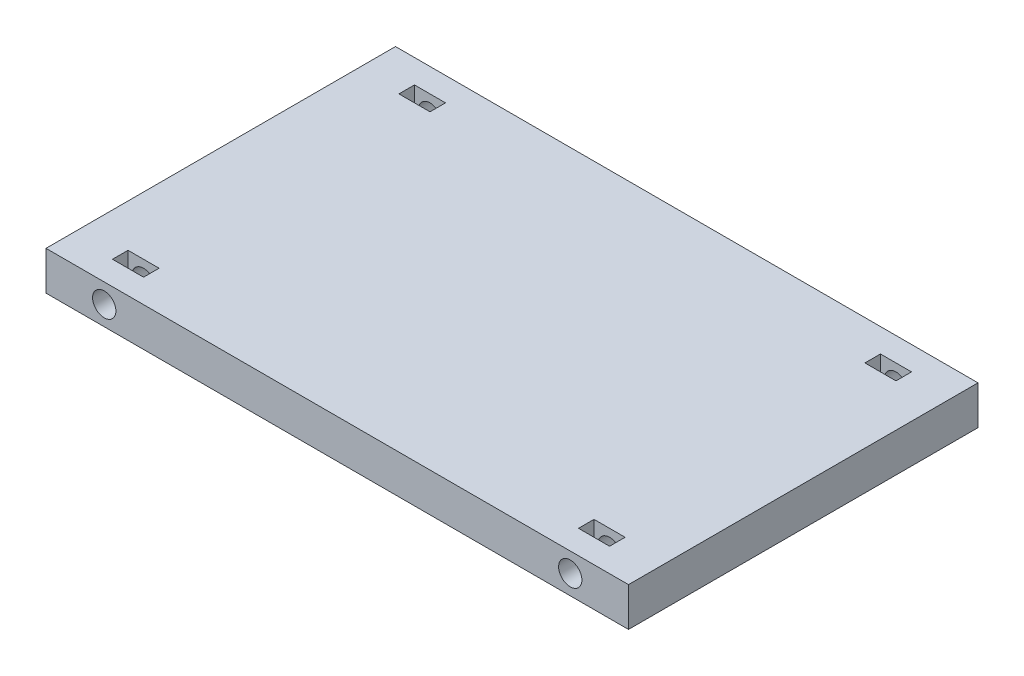
SolidWorks part; units mm, degrees
ref_plane "Front Plane" through (0, 0, 0) normal (0, 0, 1) x (1, 0, 0)
ref_plane "Top Plane" through (0, 0, 0) normal (0, 1, 0) x (1, 0, 0)
ref_plane "Right Plane" through (0, 0, 0) normal (1, 0, 0) x (0, 0, -1)
sketch "Sketch1" plane through (0, 0, 0) normal (0, 1, 0) x (1, 0, 0)
  line L0 (75, 90) -> (75, -10.3803) construction
  line L1 (0, 0) -> (150, 0)
  line L2 (0, 0) -> (0, 90)
  line L3 (0, 90) -> (150, 90)
  line L4 (150, 0) -> (150, 90)
  line L5 (75, -10.3803) -> (75, 39.8099) construction
  line L6 (0, 45) -> (160.1026, 45) construction
  line L7 (139, 10.1206) -> (139, 6.1206)
  line L8 (11, 83.8794) -> (19, 83.8794)
  line L9 (11, 83.8794) -> (11, 79.8794)
  line L10 (11, 79.8794) -> (19, 79.8794)
  line L11 (19, 83.8794) -> (19, 79.8794)
  line L12 (131, 79.8794) -> (139, 79.8794)
  line L13 (131, 79.8794) -> (131, 83.8794)
  line L14 (131, 83.8794) -> (139, 83.8794)
  line L15 (139, 79.8794) -> (139, 83.8794)
  line L16 (131, 6.1206) -> (139, 6.1206)
  line L17 (131, 10.1206) -> (131, 6.1206)
  line L18 (131, 10.1206) -> (139, 10.1206)
  line L19 (19, 6.1206) -> (19, 10.1206)
  line L20 (11, 10.1206) -> (19, 10.1206)
  line L21 (11, 6.1206) -> (11, 10.1206)
  line L22 (11, 6.1206) -> (19, 6.1206)
  point P14 (11, 81.8794)
  dimension "D1" = 90
  dimension "D2" = 150
  dimension "D3" = 4
  dimension "D4" = 8
  dimension "D5" = 11
  dimension "D6" = 8
  dimension "D7" = 112
extrude "Boss-Extrude1" add sketch "Sketch1" along normal blind 10
sketch "Sketch3" plane through (0, 0, 0) normal (0, 0, 1) x (1, 0, 0)
  line L1 (0, 5) -> (160.3195, 5) construction
  line L2 (0, 10) -> (0, 0) construction
  line L3 (75, 10) -> (75, 0) construction
  line L4 (0, 10) -> (150, 10) construction
  line L5 (0, 0) -> (150, 0) construction
  circle A0 centre (15, 5) radius 3
  circle A1 centre (135, 5) radius 3
  dimension "D1" = 6
  dimension "D3" = 6
  dimension "D2" = 15
  dimension "D4" = 120
extrude "Cut-Extrude1" cut sketch "Sketch3" against normal blind 15
sketch "Sketch4" plane through (0, 0, -90) normal (0, 0, -1) x (-1, 0, 0)
  line L0 (0, 5) -> (-154.9348, 5) construction
  line L1 (0, 10) -> (0, 0) construction
  circle A0 centre (-15, 5) radius 3
  circle A1 centre (-135, 5) radius 3
  dimension "D1" = 6
  dimension "D3" = 6
  dimension "D2" = 15
  dimension "D4" = 120
extrude "Cut-Extrude2" cut sketch "Sketch4" against normal blind 15
sketch "Sketch5" plane through (0, 10, 0) normal (0, 1, 0) x (1, 0, 0)
  text T0 "<b>Control Panel</b>" font "Century Gothic" height 15
